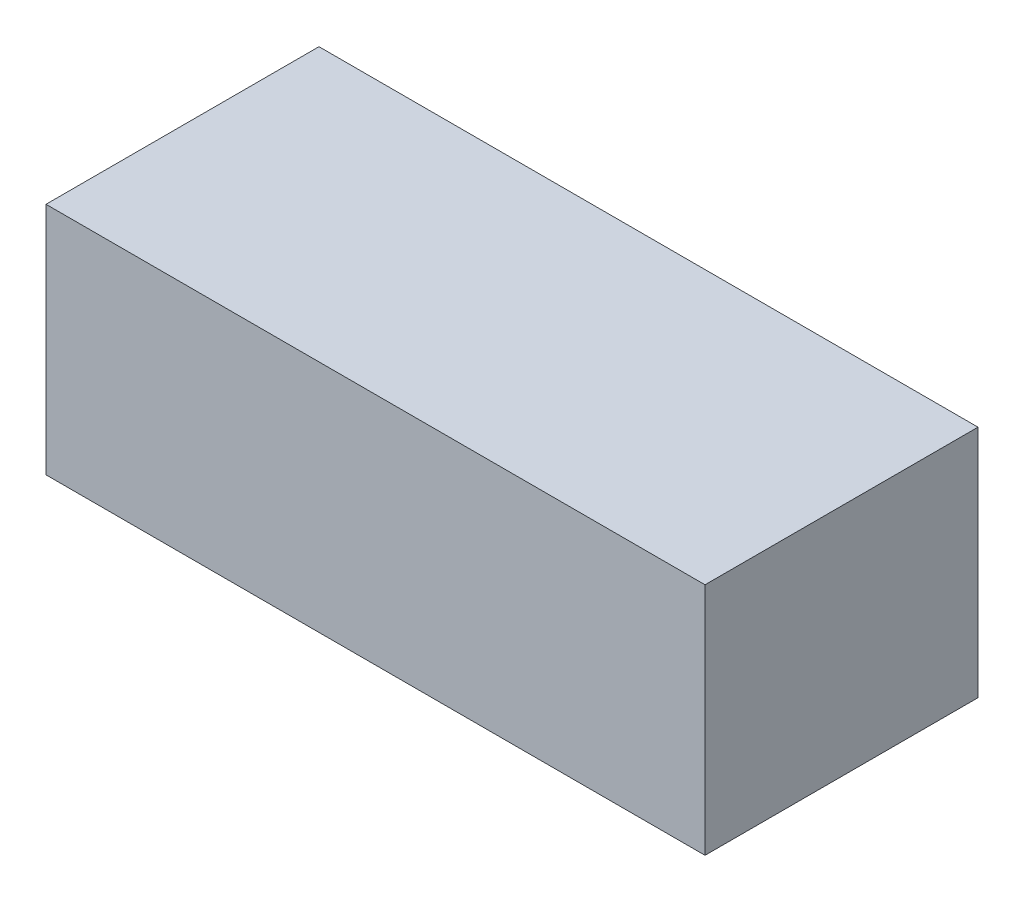
SolidWorks part; units mm, degrees
ref_plane "Front Plane" through (0, 0, 0) normal (0, 0, 1) x (1, 0, 0)
ref_plane "Top Plane" through (0, 0, 0) normal (0, 1, 0) x (1, 0, 0)
ref_plane "Right Plane" through (0, 0, 0) normal (1, 0, 0) x (0, 0, -1)
other "Bounding Box"
ref_plane "Default Plane" through (-8.9266, -12.7485, 0) normal (-0.1736, 0.9848, 0) x (0.9848, 0.1736, 0)
sketch "Sketch1" plane through (0, 0, 0) normal (0, 1, 0) x (1, 0, 0)
  line L1 (-28.575, -11.8364) -> (28.575, -11.8364)
  line L2 (-28.575, -11.8364) -> (-28.575, 11.8364)
  line L3 (-28.575, 11.8364) -> (28.575, 11.8364)
  line L4 (28.575, -11.8364) -> (28.575, 11.8364)
  line L5 (-28.575, -11.8364) -> (28.575, 11.8364) construction
  line L6 (-28.575, 11.8364) -> (28.575, -11.8364) construction
  point P0 (0, 0)
  dimension "D1" = 23.6728
  dimension "D2" = 57.15
extrude "Boss-Extrude1" add sketch "Sketch1" along normal mid plane 20.32
